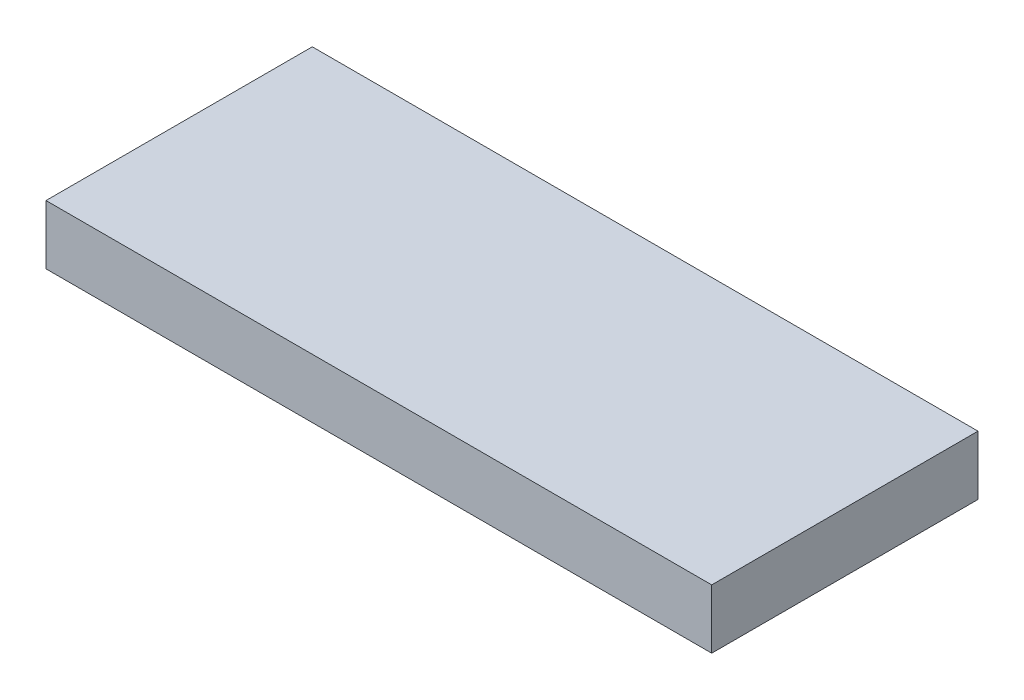
SolidWorks part; units mm, degrees
ref_plane "Front Plane" through (0, 0, 0) normal (0, 0, 1) x (1, 0, 0)
ref_plane "Top Plane" through (0, 0, 0) normal (0, 1, 0) x (1, 0, 0)
ref_plane "Right Plane" through (0, 0, 0) normal (1, 0, 0) x (0, 0, -1)
sketch "Sketch1" plane through (0, 0, 0) normal (0, 1, 0) x (1, 0, 0)
  line L1 (-225, -90) -> (225, -90)
  line L2 (-225, -90) -> (-225, 90)
  line L3 (-225, 90) -> (225, 90)
  line L4 (225, -90) -> (225, 90)
  line L5 (-225, -90) -> (225, 90) construction
  line L6 (-225, 90) -> (225, -90) construction
  point P0 (0, 0)
  dimension "D1" = 180
  dimension "D2" = 450
extrude "Boss-Extrude1" add sketch "Sketch1" along normal blind 40
